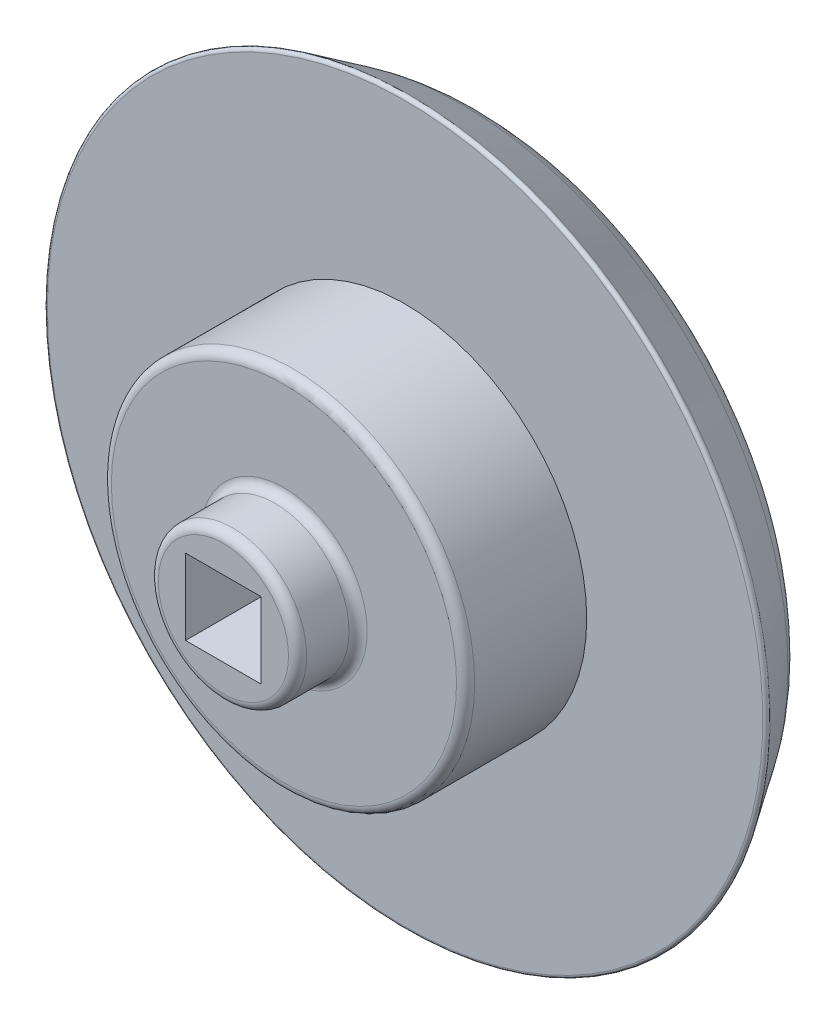
SolidWorks part; units mm, degrees
ref_plane "Front Plane" through (0, 0, 0) normal (0, 0, 1) x (1, 0, 0)
ref_plane "Top Plane" through (0, 0, 0) normal (0, 1, 0) x (1, 0, 0)
ref_plane "Right Plane" through (0, 0, 0) normal (1, 0, 0) x (0, 0, -1)
sketch "Sketch1" plane through (0, 0, 0) normal (0, 1, 0) x (1, 0, 0)
  line L0 (0, 5.683) -> (0, -1.937)
  line L1 (0, -1.937) -> (30.48, -1.937)
  line L2 (30.48, -1.937) -> (25.4, 5.683)
  line L3 (25.4, 5.683) -> (0, 5.683)
  dimension "D1" = 25.4
  dimension "D2" = 30.48
  dimension "D3" = 0
  dimension "D4" = 7.62
revolve "Revolve1" add sketch "Sketch1" angle 360 about L0
sketch "Sketch3" plane through (0, 0, 1.937) normal (0, 0, 1) x (1, 0, 0)
  circle A0 centre (0, 0) radius 15.24
  dimension "D1" = 30.48
extrude "Boss-Extrude2" add sketch "Sketch3" along normal blind 10.16
sketch "Sketch4" plane through (0, 0, 12.097) normal (0, 0, 1) x (1, 0, 0)
  circle A0 centre (0, 0) radius 6.2241
extrude "Boss-Extrude3" add sketch "Sketch4" along normal blind 5.08
sketch "Sketch5" plane through (0, 0, -5.683) normal (0, 0, -1) x (-1, 0, 0)
  circle A0 centre (0, 0) radius 12.7
  dimension "D1" = 25.4
extrude "Cut-Extrude1" cut sketch "Sketch5" against normal blind 5.08
fillet "Fillet1" radius 6.096 1 edges at (-25.4, 0, -5.683)
fillet "Fillet2" radius 0.762 3 edges at (15.24, 0, 12.097) (6.2241, 0, 12.097) (6.2241, 0, 17.177)
fillet "Fillet3" radius 0.254 1 edges at (-30.48, 0, 1.937)
sketch "Sketch6" plane through (0, 0, 17.177) normal (0, 0, 1) x (1, 0, 0)
  line L1 (-3.175, 3.175) -> (3.175, 3.175)
  line L2 (-3.175, 3.175) -> (-3.175, -3.175)
  line L3 (-3.175, -3.175) -> (3.175, -3.175)
  line L4 (3.175, 3.175) -> (3.175, -3.175)
  dimension "D1" = 6.35
  dimension "D2" = 6.35
  dimension "D3" = 3.175
  dimension "D4" = 3.175
extrude "Cut-Extrude2" cut sketch "Sketch6" against normal blind 11
